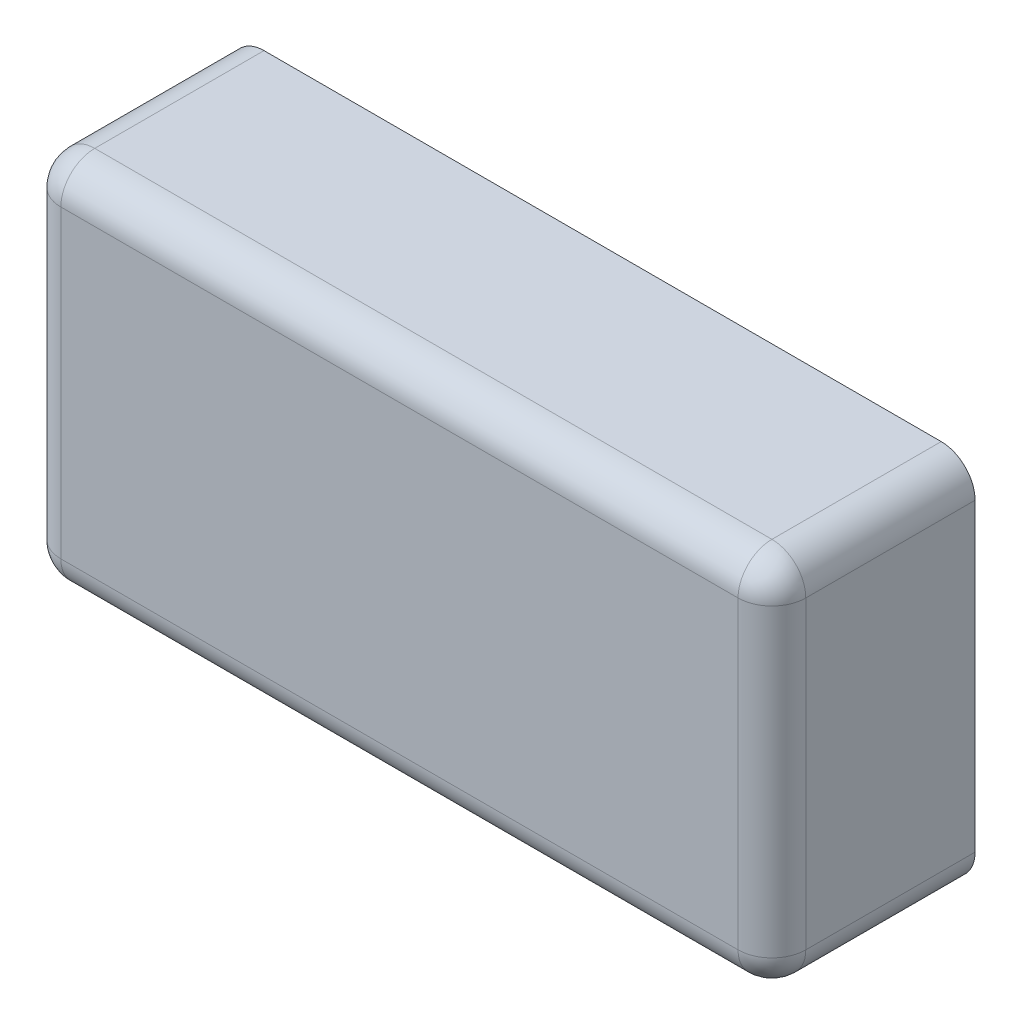
SolidWorks part; units mm, degrees
material "Silicon"
ref_plane "Front Plane" through (0, 0, 0) normal (0, 0, 1) x (1, 0, 0)
ref_plane "Top Plane" through (0, 0, 0) normal (0, 1, 0) x (1, 0, 0)
ref_plane "Right Plane" through (0, 0, 0) normal (1, 0, 0) x (0, 0, -1)
sketch "Sketch1" plane through (0, 0, 0) normal (0, 0, 1) x (1, 0, 0)
  line L1 (-49.0607, 24.571) -> (60.9393, 24.571)
  line L2 (-49.0607, 24.571) -> (-49.0607, -30.429)
  line L3 (-49.0607, -30.429) -> (60.9393, -30.429)
  line L4 (60.9393, 24.571) -> (60.9393, -30.429)
  dimension "D1" = 110
  dimension "D2" = 55
extrude "Boss-Extrude1" add sketch "Sketch1" along normal blind 30
fillet "Fillet1" radius 5 8 edges at (60.9393, -30.429, 15) (-49.0607, -30.429, 15) (5.9393, -30.429, 30) (60.9393, -2.929, 30) (60.9393, 24.571, 15) (-49.0607, 24.571, 15) (-49.0607, -2.929, 30) (5.9393, 24.571, 30)
